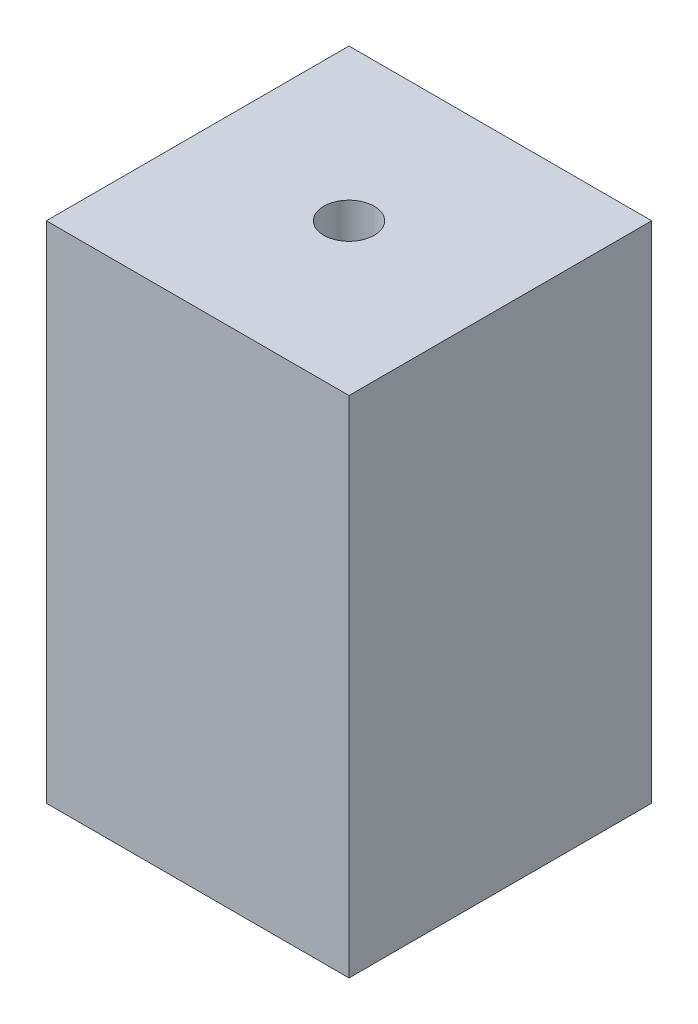
SolidWorks part; units mm, degrees
ref_plane "Front Plane" through (0, 0, 0) normal (0, 0, 1) x (1, 0, 0)
ref_plane "Top Plane" through (0, 0, 0) normal (0, 1, 0) x (1, 0, 0)
ref_plane "Right Plane" through (0, 0, 0) normal (1, 0, 0) x (0, 0, -1)
sketch "Sketch1" plane through (0, 0, 0) normal (0, 1, 0) x (1, 0, 0)
  line L1 (-15, 15) -> (15, 15)
  line L2 (-15, 15) -> (-15, -15)
  line L3 (-15, -15) -> (15, -15)
  line L4 (15, 15) -> (15, -15)
  line L5 (-15, 15) -> (15, -15) construction
  line L6 (-15, -15) -> (15, 15) construction
  point P0 (0, 0)
  dimension "D1" = 30
extrude "Boss-Extrude1" add sketch "Sketch1" along normal blind 50
sketch "Sketch2" plane through (0, 50, 0) normal (0, 1, 0) x (1, 0, 0)
  circle A0 centre (0, 0) radius 2.5
  dimension "D1" = 5
extrude "Cut-Extrude1" cut sketch "Sketch2" against normal blind 10
